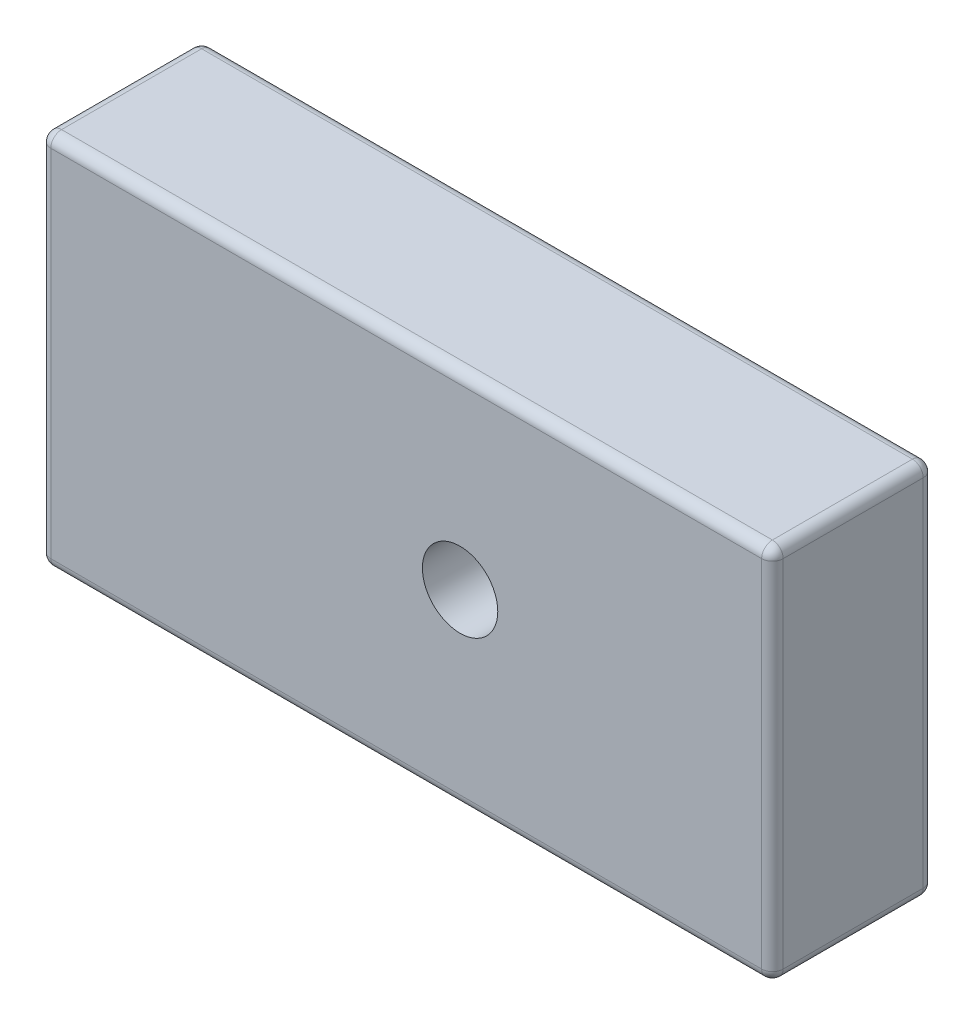
SolidWorks part; units mm, degrees
ref_plane "Plan de face" through (0, 0, 0) normal (0, 0, 1) x (1, 0, 0)
ref_plane "Plan de dessus" through (0, 0, 0) normal (0, 1, 0) x (1, 0, 0)
ref_plane "Plan de droite" through (0, 0, 0) normal (1, 0, 0) x (0, 0, -1)
sketch "Sketch1" plane through (0, 0, 0) normal (0, 0, 1) x (1, 0, 0)
  line L1 (-34, -17.5) -> (34, -17.5)
  line L2 (-34, -17.5) -> (-34, 17.5)
  line L3 (-34, 17.5) -> (34, 17.5)
  line L4 (34, -17.5) -> (34, 17.5)
  line L5 (-34, -17.5) -> (34, 17.5) construction
  line L6 (-34, 17.5) -> (34, -17.5) construction
  point P0 (0, 0)
  dimension "D1" = 68
  dimension "D2" = 35
extrude "Boss-Extrude1" add sketch "Sketch1" along normal blind 15
fillet "Fillet1" radius 1 2 edges at (-34, 0, 0) (-34, 0, 15)
fillet "Fillet2" radius 1 2 edges at (34, 0, 0) (34, 0, 15)
fillet "Fillet3" radius 1 8 edges at (-33.7071, -17.5, 14.7071) (0, -17.5, 15) (33.7071, -17.5, 14.7071) (34, -17.5, 7.5) (33.7071, -17.5, 0.2929) (0, -17.5, 0) (-33.7071, -17.5, 0.2929) (-34, -17.5, 7.5)
fillet "Fillet4" radius 1 8 edges at (-33.7071, 17.5, 14.7071) (0, 17.5, 15) (33.7071, 17.5, 14.7071) (34, 17.5, 7.5) (33.7071, 17.5, 0.2929) (0, 17.5, 0) (-33.7071, 17.5, 0.2929) (-34, 17.5, 7.5)
sketch "Sketch2" plane through (0, 0, 15) normal (0, 0, 1) x (1, 0, 0)
  circle A0 centre (5, 0) radius 3.5
  dimension "D1" = 7
extrude "Cut-Extrude1" cut sketch "Sketch2" against normal blind 5
